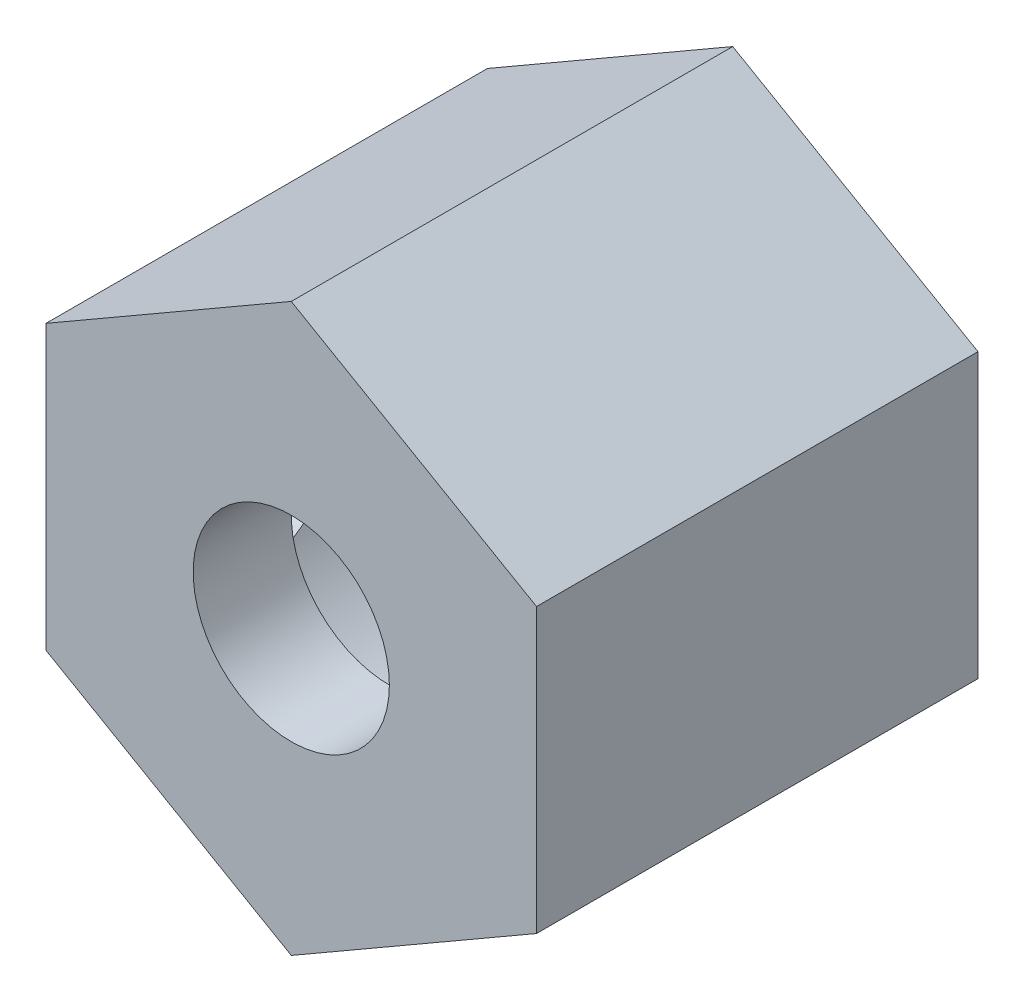
SolidWorks part; units mm, degrees
ref_plane "前视基准面" through (0, 0, 0) normal (0, 0, 1) x (1, 0, 0)
ref_plane "上视基准面" through (0, 0, 0) normal (0, 1, 0) x (1, 0, 0)
ref_plane "右视基准面" through (0, 0, 0) normal (1, 0, 0) x (0, 0, -1)
sketch "Sketch2" plane through (0, 0, 0) normal (0, 0, 1) x (1, 0, 0)
  line L1 (0, -5.7735) -> (5, -2.8868)
  line L2 (5, -2.8868) -> (5, 2.8868)
  line L3 (5, 2.8868) -> (0, 5.7735)
  line L4 (0, 5.7735) -> (-5, 2.8868)
  line L5 (-5, 2.8868) -> (-5, -2.8868)
  line L6 (-5, -2.8868) -> (0, -5.7735)
  circle A0 centre (0, 0) radius 5 construction
extrude "Boss-Extrude1" add sketch "Sketch2" along normal blind 6
sketch "Sketch3" plane through (-5, 0, 0) normal (-1, 0, 0) x (0, 0, 1)
  circle A0 centre (3, 0) radius 2
extrude "Cut-Extrude1" cut sketch "Sketch3" against normal blind 2.5
sketch "Sketch5" plane through (0, 0, 6) normal (0, 0, 1) x (1, 0, 0)
  circle A0 centre (0, 0) radius 2
extrude "Cut-Extrude5" cut sketch "Sketch5" against normal up to next
sketch "Sketch6" plane through (0, 0, 0) normal (0, 0, -1) x (-1, 0, 0)
  line L1 (0, 5.7735) -> (-5, 2.8868)
  line L2 (-5, 2.8868) -> (-5, -2.8868)
  line L3 (-5, -2.8868) -> (0, -5.7735)
  line L4 (0, -5.7735) -> (5, -2.8868)
  line L5 (5, -2.8868) -> (5, 2.8868)
  line L6 (5, 2.8868) -> (0, 5.7735)
  circle A0 centre (0, 0) radius 5 construction
  circle A1 centre (0, 0) radius 2
extrude "Boss-Extrude2" add sketch "Sketch6" along normal blind 3
sketch "Sketch7" plane through (0, 0, -3) normal (0, 0, -1) x (-1, 0, 0)
  circle A0 centre (0, 0) radius 4
extrude "Cut-Extrude6" cut sketch "Sketch7" against normal blind 7
